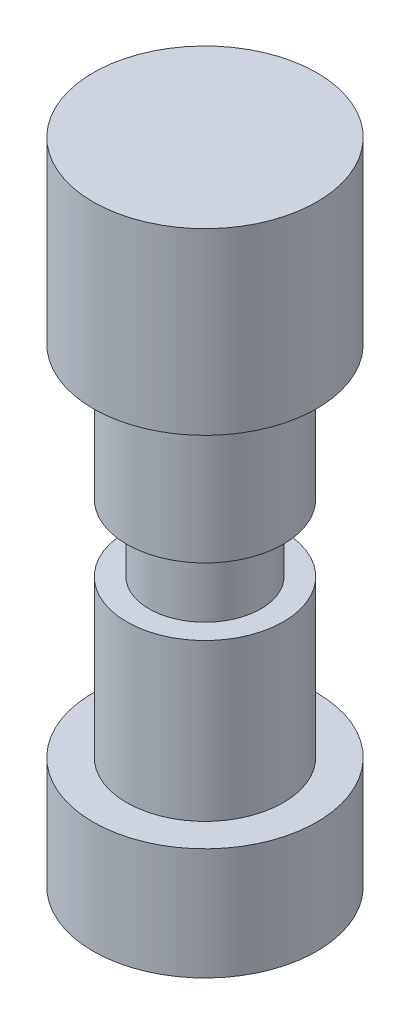
SolidWorks part; units mm, degrees
ref_plane "Alzado" through (0, 0, 0) normal (0, 0, 1) x (1, 0, 0)
ref_plane "Planta" through (0, 0, 0) normal (0, 1, 0) x (1, 0, 0)
ref_plane "Vista lateral" through (0, 0, 0) normal (1, 0, 0) x (0, 0, -1)
sketch "Croquis1" plane through (0, 0, 0) normal (0, 0, 1) x (1, 0, 0)
  line L0 (0, 0) -> (0, 35.5433) construction
  line L1 (0, 0) -> (25, 0)
  line L2 (25, 0) -> (25, -40)
  line L3 (25, -40) -> (17.5, -40)
  line L4 (17.5, -40) -> (17.5, -70)
  line L5 (17.5, -70) -> (12.5, -70)
  line L6 (12.5, -70) -> (12.5, -85)
  line L7 (12.5, -85) -> (17.5, -85)
  line L8 (17.5, -85) -> (17.5, -120)
  line L9 (17.5, -120) -> (25, -120)
  line L10 (25, -120) -> (25, -145)
  line L11 (25, -145) -> (0, -145)
  line L12 (0, -145) -> (0, 0)
  dimension "D1" = 25
  dimension "D2" = 17.5
  dimension "D3" = 40
  dimension "D4" = 12.5
  dimension "D5" = 30
  dimension "D6" = 15
  dimension "D7" = 35
  dimension "D8" = 25
revolve "Revolución1" add sketch "Croquis1" angle 360 about L0
